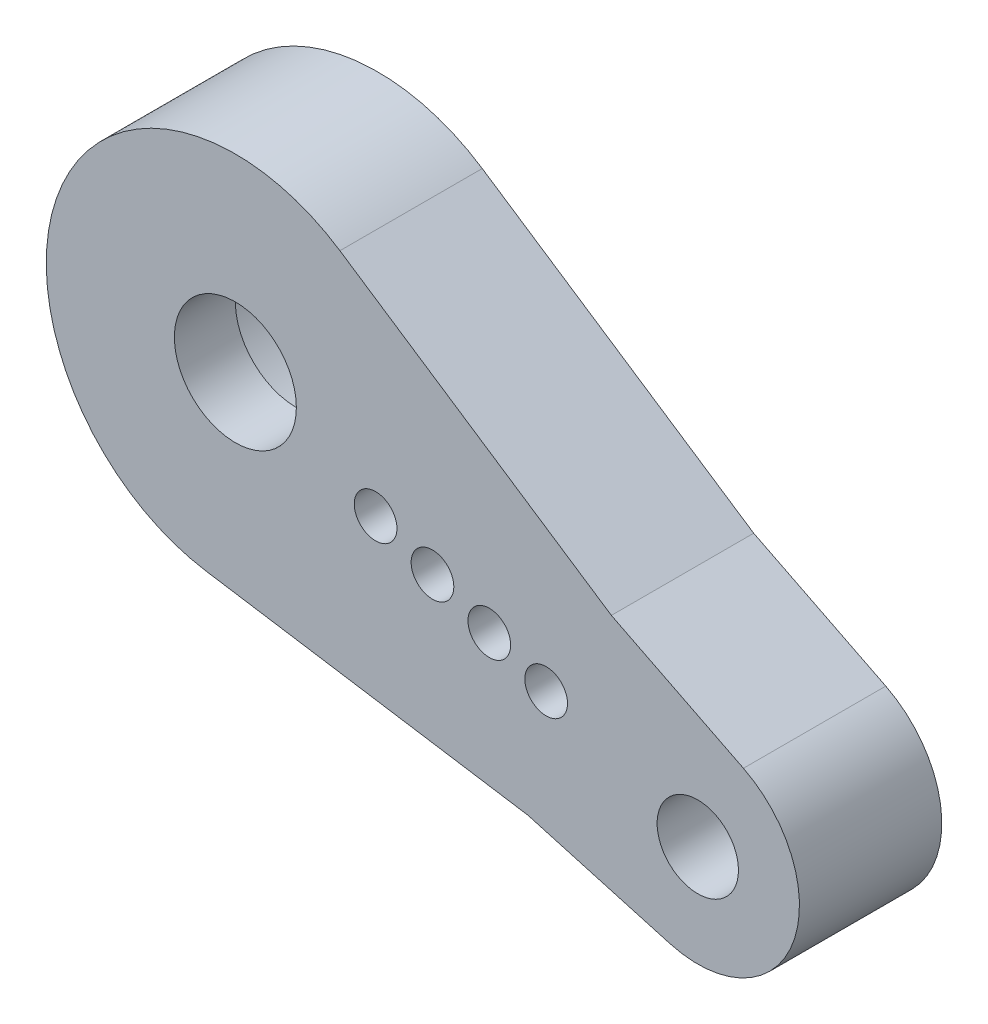
SolidWorks part; units mm, degrees
ref_plane "Спереди" through (0, 0, 0) normal (0, 0, 1) x (1, 0, 0)
ref_plane "Сверху" through (0, 0, 0) normal (0, 1, 0) x (1, 0, 0)
ref_plane "Справа" through (0, 0, 0) normal (1, 0, 0) x (0, 0, -1)
sketch "Эскиз1" plane through (0, 0, 0) normal (0, 0, 1) x (1, 0, 0)
  line L2 (14.8984, -8.4111) -> (-2.8278, -5.6297) construction
  line L3 (3.3171, 4.9997) -> (16.6681, -3.8581) construction
  line L4 (3.4829, 5.2497) -> (16.8339, -3.6081)
  line L5 (14.8519, -8.7075) -> (-0.9766, -6.2238)
  line L6 (14.8984, -8.4111) -> (-0.9301, -5.9275) construction
  line L7 (0, 0) -> (15.286, -5.9413) construction
  line L8 (14.3869, -11.6712) -> (-1.4416, -9.1876)
  line L9 (5.1415, 7.7495) -> (18.4925, -1.1083)
  circle A0 centre (0, 0) radius 3 construction
  arc A3 (14.8984, -8.4111) -> (16.6681, -3.8581) centre (15.286, -5.9413) ccw construction
  arc A4 (14.8519, -8.7075) -> (16.8339, -3.6081) centre (15.286, -5.9413) ccw
  arc A5 (3.4829, 5.2497) -> (-0.9766, -6.2238) centre (0, 0) ccw
  circle A6 centre (6.8973, -2.6808) radius 0.75 construction
  circle A8 centre (12.4897, -4.8545) radius 0.75 construction
  circle A9 centre (15.286, -5.9413) radius 0.75 construction
  circle A10 centre (9.6935, -3.7677) radius 0.75 construction
  arc A11 (5.1415, 7.7495) -> (-1.4416, -9.1876) centre (0, 0) ccw
  arc A12 (14.3869, -11.6712) -> (18.4925, -1.1083) centre (15.286, -5.9413) ccw
  dimension "D1" = 6
  dimension "D2" = 0.3
  dimension "D3" = 3
extrude "Бобышка-Вытянуть1" add sketch "Эскиз1" along normal blind 4
sketch "Эскиз2" plane through (0, 0, 4) normal (0, 0, 1) x (1, 0, 0)
  line L0 (-1.4416, -9.1876) -> (14.3869, -11.6712) construction
  line L1 (18.4925, -1.1083) -> (5.1415, 7.7495) construction
  line L2 (-1.4416, -9.1876) -> (14.3869, -11.6712)
  line L3 (18.4925, -1.1083) -> (5.1415, 7.7495)
  arc A0 (14.3869, -11.6712) -> (18.4925, -1.1083) centre (15.286, -5.9413) ccw construction
  arc A1 (5.1415, 7.7495) -> (-1.4416, -9.1876) centre (0, 0) ccw construction
  arc A2 (14.3869, -11.6712) -> (18.4925, -1.1083) centre (15.286, -5.9413) ccw
  arc A3 (5.1415, 7.7495) -> (-1.4416, -9.1876) centre (0, 0) ccw
  circle A4 centre (0, 0) radius 3
  circle A5 centre (6.8973, -2.6808) radius 1.05
  circle A6 centre (9.6935, -3.7677) radius 1.05
  circle A7 centre (12.4897, -4.8545) radius 1.05
  circle A8 centre (15.286, -5.9413) radius 1.05
  dimension "D1" = 2.1
  dimension "D2" = 6
extrude "Бобышка-Вытянуть2" add sketch "Эскиз2" along normal blind 3
sketch "Эскиз3" plane through (0, 0, 7) normal (0, 0, 1) x (1, 0, 0)
  line L0 (0, 0) -> (15.286, -5.9413) construction
  line L1 (15.286, -5.9413) -> (22.7425, -8.8395) construction
  line L2 (18.4925, -1.1083) -> (24.9874, -4.3718)
  line L3 (14.3869, -11.6712) -> (21.381, -13.6506)
  arc A0 (14.3869, -11.6712) -> (18.4925, -1.1083) centre (15.286, -5.9413) ccw construction
  arc A1 (14.3869, -11.6712) -> (18.4925, -1.1083) centre (15.286, -5.9413) ccw
  circle A2 centre (22.7425, -8.8395) radius 2
  arc A3 (21.381, -13.6506) -> (24.9874, -4.3718) centre (22.7425, -8.8395) ccw
  dimension "D2" = 4
  dimension "D3" = 10
  dimension "D1" = 8
extrude "Бобышка-Вытянуть3" add sketch "Эскиз3" against normal blind 7
